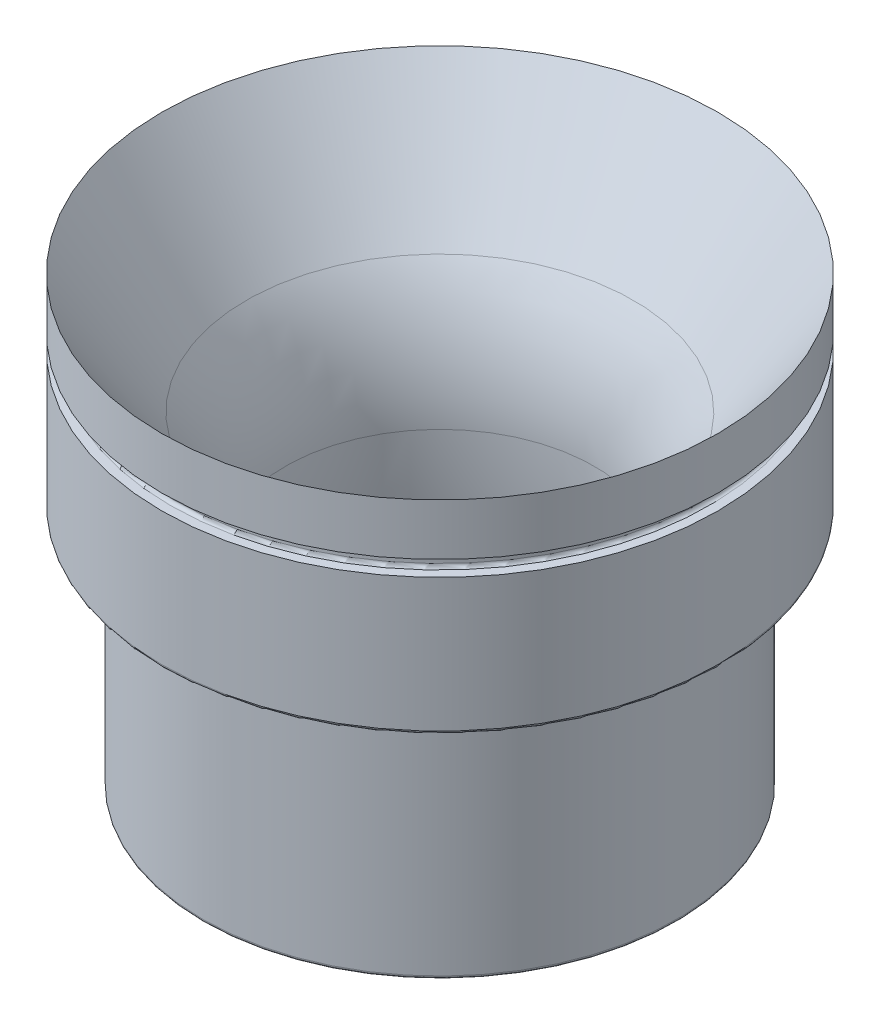
SolidWorks part; units mm, degrees
material "C (Graphite)"
ref_plane "Front Plane" through (0, 0, 0) normal (0, 0, 1) x (1, 0, 0)
ref_plane "Top Plane" through (0, 0, 0) normal (0, 1, 0) x (1, 0, 0)
ref_plane "Right Plane" through (0, 0, 0) normal (1, 0, 0) x (0, 0, -1)
sketch "Sketch4" plane through (0, 0, 0) normal (1, 0, 0) x (0, 0, -1)
  line L0 (0, 0) -> (0, -131.2074) construction
  line L1 (34.2837, 0) -> (23.8732, -14.8676)
  line L2 (19.05, -81.8664) -> (19.05, -89.5402) construction
  line L3 (22.2956, -54.8174) -> (51.1382, -162.4597) construction
  line L17 (34.2837, 0) -> (34.2837, -25.0595)
  line L18 (34.2837, -25.0595) -> (29.1846, -25.0595)
  line L19 (29.1846, -25.0595) -> (29.1846, -54.8073)
  line L20 (29.1846, -54.8073) -> (22.2928, -54.8073)
  arc A1 (23.8732, -14.8676) -> (19.05, -30.1649) centre (45.72, -30.1649) ccw construction
  arc A2 (19.05, -30.1649) -> (22.2956, -54.8174) centre (114.3, -30.1649) ccw construction
  arc A3 (19.05, -30.1649) -> (22.2928, -54.8073) centre (114.3, -30.1649) ccw
  arc A4 (19.05, -30.1649) -> (23.8732, -14.8676) centre (45.72, -30.1649) cw
  dimension "D4" = 26.67
  dimension "D6" = 95.25
  dimension "D3" = 35
  dimension "D5" = 38.1
  dimension "D7" = 15
  dimension "D15" = 3.2456
  dimension "D19" = 10.1346
  dimension "D20" = 5.1054
  dimension "D11" = 68.5673
  dimension "D24" = 58.3692
  dimension "D8" = 29.7478
revolve "Revolve1" add sketch "Sketch4" angle 360 about L0
sketch "Sketch6" plane through (0, 0, 0) normal (1, 0, 0) x (0, 0, -1)
  line L0 (34.2837, -6.35) -> (32.766, -6.35)
  line L1 (32.766, -6.35) -> (32.766, -8.255)
  line L2 (32.766, -8.255) -> (34.2837, -8.255)
  line L3 (34.2837, -8.255) -> (34.2837, -6.35)
  line L5 (-34.2837, 0) -> (34.2837, 0) construction
  line L6 (0, 11.3644) -> (0, 4.9299) construction
  line L7 (-34.2837, 0) -> (34.2837, 0) construction
  dimension "D1" = 65.532
  dimension "D2" = 1.905
  dimension "D3" = 6.35
revolve "Spring Groove" cut sketch "Sketch6" angle 360 about L6
fillet "Tool Radius" radius 0.4064 5 edges at (0, -54.8073, 29.1846) (0, -25.0595, 34.2837) (0, -6.35, 32.766) (0, -8.255, 32.766) (0, -25.0595, 29.1846)
equation "\"Dc\"= 114.30mm"
equation "\"Dt\"= 38.1mm"
equation "\"R1\"= 26.67mm"
equation "\"R2\"= 92mm"
equation "\"b\"= 35deg"
equation "\"Rn\"= 95.25mm"
equation "\"Tn\"= 15deg"
equation "\"Te\"= 3deg"
equation "\"De\"= 87.31mm"
equation "\"Le\"= 146.71mm"
equation "\"D5@Sketch4\"=\"Dt\""
equation "\"WallThickness\"=0.5"
equation "\"Rt\"=1.5"
